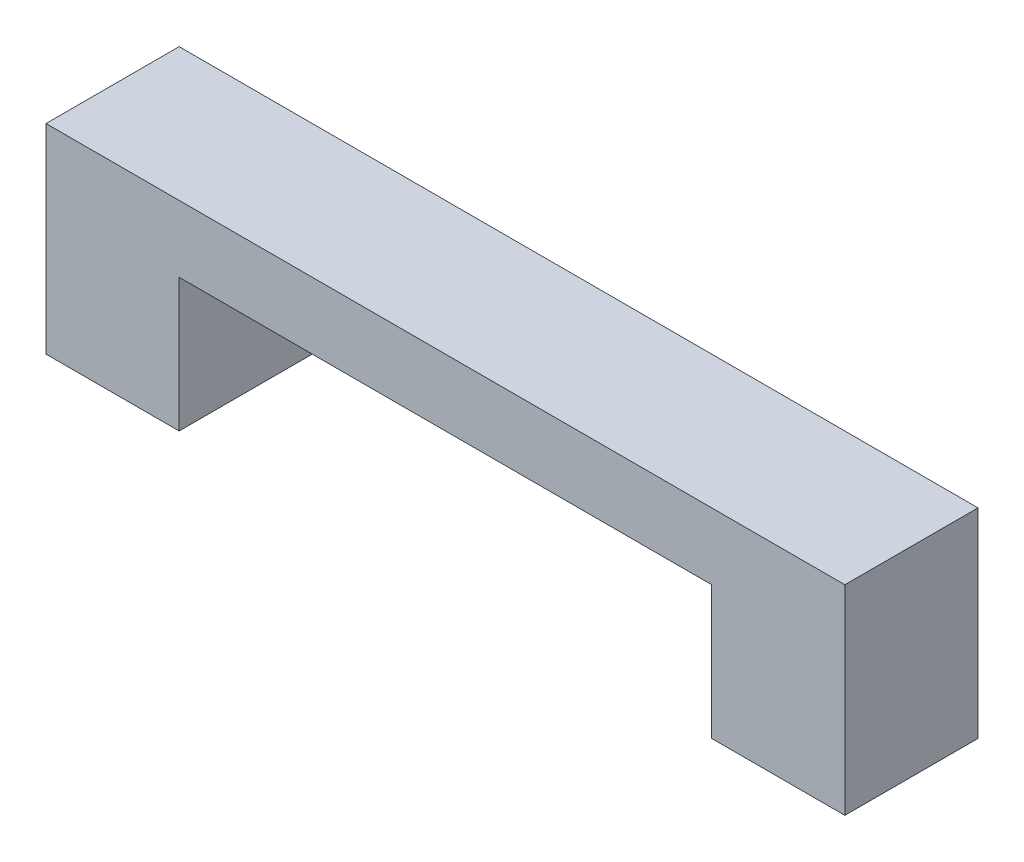
SolidWorks part; units mm, degrees
ref_plane "Plan de face" through (0, 0, 0) normal (0, 0, 1) x (1, 0, 0)
ref_plane "Plan de dessus" through (0, 0, 0) normal (0, 1, 0) x (1, 0, 0)
ref_plane "Plan de droite" through (0, 0, 0) normal (1, 0, 0) x (0, 0, -1)
sketch "Esquisse1" plane through (0, 0, 0) normal (0, 0, 1) x (1, 0, 0)
  line L0 (0, 0) -> (-2, 0)
  line L2 (0, 0) -> (0, 2)
  line L3 (0, 2) -> (8, 2)
  line L4 (8, 0) -> (8, 2)
  line L5 (-2, 0) -> (-2, 3)
  line L6 (-2, 3) -> (10, 3)
  line L7 (10, 3) -> (10, 0)
  line L8 (10, 0) -> (8, 0)
  dimension "D1" = 2
  dimension "D2" = 2
  dimension "D3" = 12
  dimension "D4" = 3
  dimension "D5" = 2
  dimension "D6" = 3
extrude "Boss.-Extru.1" add sketch "Esquisse1" along normal blind 2
